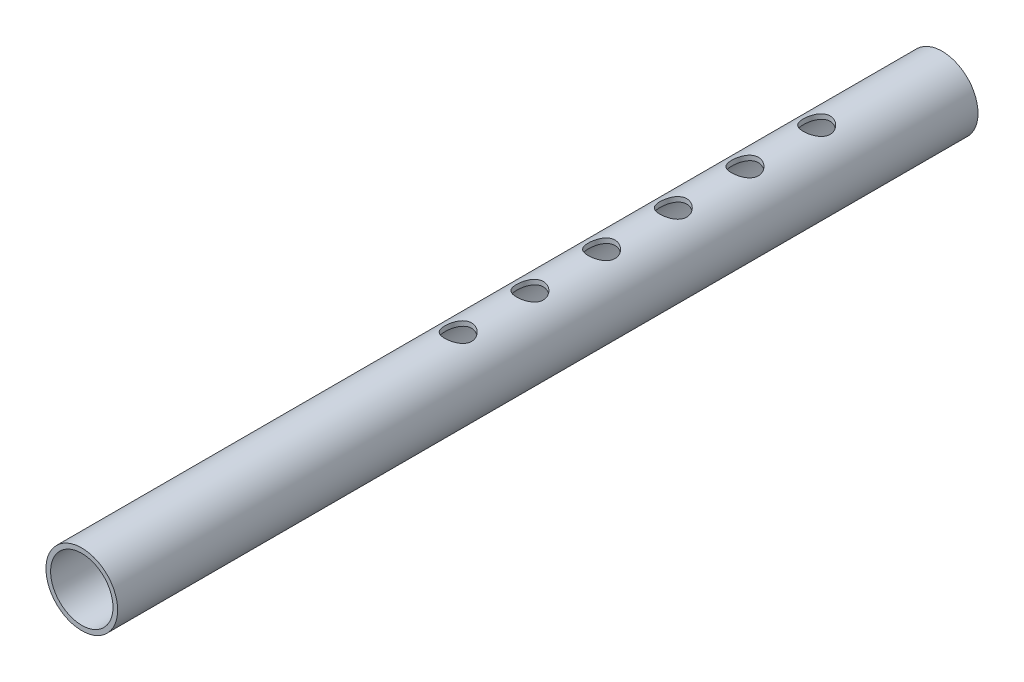
SolidWorks part; units mm, degrees
ref_plane "Front Plane" through (0, 0, 0) normal (0, 0, 1) x (1, 0, 0)
ref_plane "Top Plane" through (0, 0, 0) normal (0, 1, 0) x (1, 0, 0)
ref_plane "Right Plane" through (0, 0, 0) normal (1, 0, 0) x (0, 0, -1)
sketch "Sketch1" plane through (0, 0, 0) normal (0, 0, 1) x (1, 0, 0)
  line L0 (12.7, 0) -> (11.049, 0) construction
  line L1 (-12.7, 0) -> (12.7, 0) construction
  dimension "OD" = 25.4
  dimension "Wall Thickness" = 1.651
sketch "Sketch2" plane through (0, 0, 0) normal (1, 0, 0) x (0, 0, -1)
  line L0 (304.8, 0) -> (-304.8, 0)
  point P4 (0, 0)
  dimension "Length" = 609.6
sketch "Sketch3" plane through (0, 0, 0) normal (0, 0, 1) x (1, 0, 0)
  circle A0 centre (0, 0) radius 12.7
  circle A1 centre (0, 0) radius 11.049
extrude "Boss-Extrude1" add sketch "Sketch3" along normal up to vertex (304.8 mm away) up to point (0, 0, 304.8)
sketch "Sketch4" plane through (0, 0, 0) normal (0, 1, 0) x (1, 0, 0)
  circle A0 centre (0, -44.45) radius 4.7625
  circle A1 centre (0, -69.85) radius 4.7625
  circle A2 centre (0, -95.25) radius 4.7625
  circle A3 centre (0, -120.65) radius 4.7625
  circle A4 centre (0, -146.05) radius 4.7625
  circle A5 centre (0, -171.45) radius 4.7625
  dimension "D1" = 9.525
  dimension "D2" = 44.45
  dimension "D3" = 6
extrude "Cut-Extrude1" cut sketch "Sketch4" against normal through all both and the other way through all
